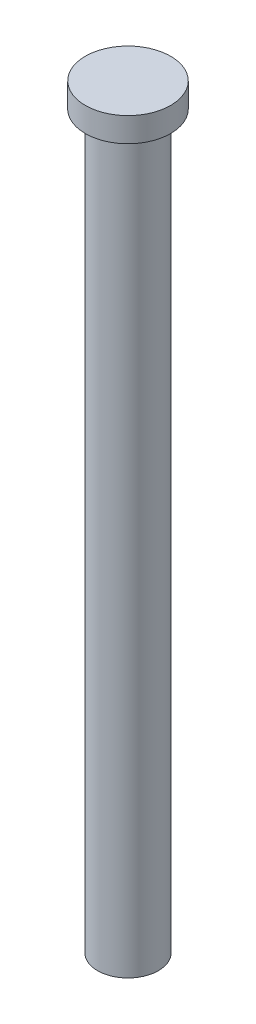
SolidWorks part; units mm, degrees
ref_plane "Front Plane" through (0, 0, 0) normal (0, 0, 1) x (1, 0, 0)
ref_plane "Top Plane" through (0, 0, 0) normal (0, 1, 0) x (1, 0, 0)
ref_plane "Right Plane" through (0, 0, 0) normal (1, 0, 0) x (0, 0, -1)
sketch "Sketch1" plane through (0, 0, 0) normal (0, 1, 0) x (1, 0, 0)
  circle A0 centre (0, 0) radius 6.35
  dimension "D1" = 12.7
extrude "Boss-Extrude1" add sketch "Sketch1" along normal blind 152.4 contours A0
sketch "Sketch2" plane through (0, 152.4, 0) normal (0, 1, 0) x (1, 0, 0)
  circle A0 centre (0, 0) radius 8.89
  dimension "D1" = 17.78
extrude "Boss-Extrude2" add sketch "Sketch2" along normal blind 5.08
